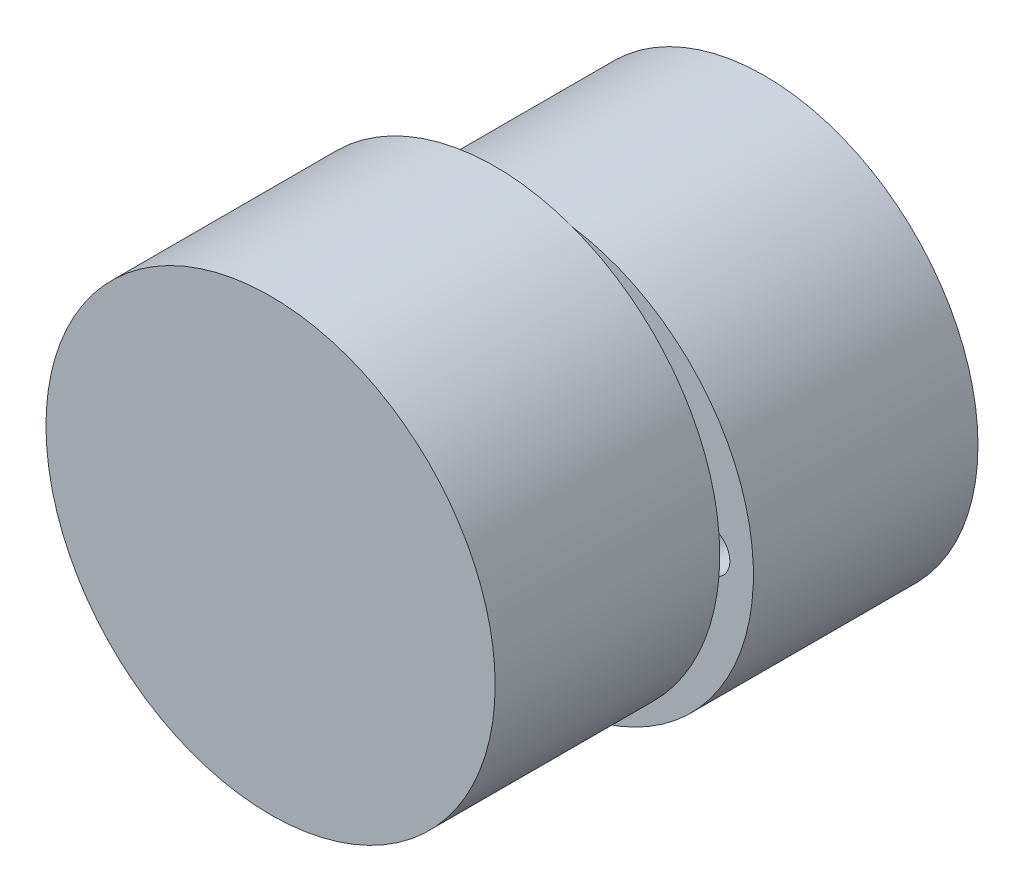
SolidWorks part; units mm, degrees
ref_plane "Front Plane" through (0, 0, 0) normal (0, 0, 1) x (1, 0, 0)
ref_plane "Top Plane" through (0, 0, 0) normal (0, 1, 0) x (1, 0, 0)
ref_plane "Right Plane" through (0, 0, 0) normal (1, 0, 0) x (0, 0, -1)
sketch "Sketch1" plane through (0, 0, 0) normal (0, 0, 1) x (1, 0, 0)
  circle A19 centre (0, 0) radius 9.5
  circle A20 centre (0, 0) radius 1.6
  circle A21 centre (0, 0) radius 7.5 construction
  circle A22 centre (-7.5, 0) radius 0.95
  circle A23 centre (-5.3033, 5.3033) radius 0.95
  circle A24 centre (0, 7.5) radius 0.95
  circle A25 centre (5.3033, 5.3033) radius 0.95
  circle A26 centre (7.5, 0) radius 0.95
  circle A27 centre (5.3033, -5.3033) radius 0.95
  circle A28 centre (0, -7.5) radius 0.95
  circle A29 centre (-5.3033, -5.3033) radius 0.95
  point P50 (0, 0)
  dimension "D1" = 19
  dimension "D2" = 3.2
  dimension "D3" = 15
  dimension "D4" = 1.9
  dimension "D5" = 8
extrude "Boss-Extrude1" add sketch "Sketch1" along normal blind 10
sketch "Sketch2" plane through (0, 0, 10) normal (0, 0, 1) x (1, 0, 0)
  circle A0 centre (-2, 0) radius 10
  dimension "D2" = 20
  dimension "D1" = 2
extrude "Boss-Extrude2" add sketch "Sketch2" along normal blind 10
sketch "Sketch5" plane through (0, 0, 0) normal (0, 0, -1) x (-1, 0, 0)
  circle A0 centre (0, 0) radius 5.5
  dimension "D1" = 11
extrude "Cut-Extrude1" cut sketch "Sketch5" against normal blind 1.2
sketch "Sketch6" plane through (0, 0, 20) normal (0, 0, 1) x (1, 0, 0)
  circle A0 centre (0, 0) radius 5
  dimension "D1" = 10
extrude "Boss-Extrude3" [suppressed] add sketch "Sketch6" along normal blind 10
